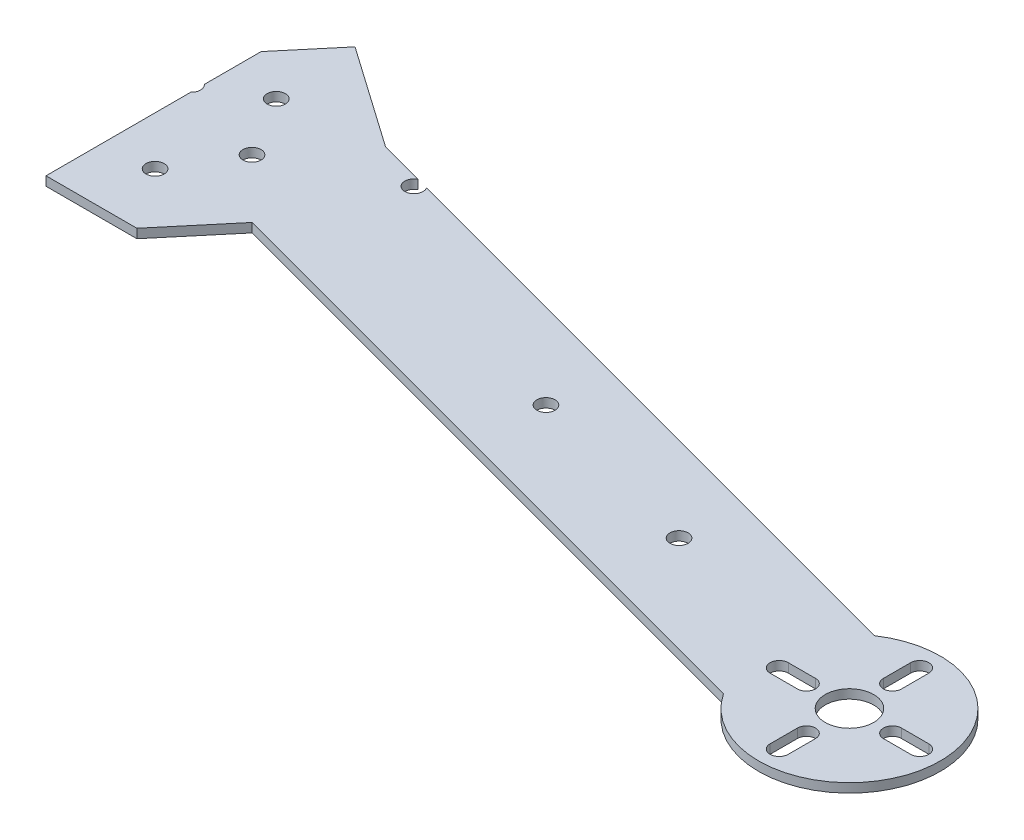
SolidWorks part; units mm, degrees
other "Markup1"
sketch "Sketch5" plane through (0, 1.5, 8.4265) normal (-0.2691, 0.6708, 0.6911) x (0.9345, 0.0084, 0.3557)
ref_plane "Front Plane" through (0, 0, 0) normal (0, 0, 1) x (1, 0, 0)
ref_plane "Top Plane" through (0, 0, 0) normal (0, 1, 0) x (1, 0, 0)
ref_plane "Right Plane" through (0, 0, 0) normal (1, 0, 0) x (0, 0, -1)
sketch "Sketch2" plane through (0, 0, 0) normal (0, 1, 0) x (1, 0, 0)
  line L25 (7.0707, -17.6306) -> (28.2625, -17.6306) construction
  line L26 (142.4295, -80.5981) -> (142.4295, -86.6558) construction
  line L27 (147.7774, -80.5981) -> (142.4295, -80.5981) construction
  line L28 (136.0028, -80.5981) -> (147.7774, -80.5981) construction
  line L29 (23.6776, -60.4195) -> (23.8633, -38.593) construction
  line L30 (0, -46.8792) -> (0, -70.7611)
  line L31 (142.4295, -80.5981) -> (142.4295, -75.2609)
  line L32 (23.8633, -38.593) -> (134.0979, -68.1247)
  line L33 (7.0707, -26.8346) -> (23.8633, -38.593)
  line L34 (0, -35.2611) -> (7.0707, -26.8346)
  line L35 (23.6776, -60.4195) -> (129.9295, -88.8896)
  line L36 (15, -70.7611) -> (23.6776, -60.4195)
  line L37 (0, -70.7611) -> (15, -70.7611)
  line L38 (0, -35.2611) -> (0, -44.6431)
  line L39 (142.4295, -73.4981) -> (142.4295, -68.9981) construction
  line L40 (143.9295, -73.4981) -> (143.9295, -68.9981)
  line L41 (140.9295, -73.4981) -> (140.9295, -68.9981)
  line L42 (149.5295, -80.5981) -> (154.0295, -80.5981) construction
  line L43 (149.5295, -82.0981) -> (154.0295, -82.0981)
  line L44 (149.5295, -79.0981) -> (154.0295, -79.0981)
  line L45 (142.4295, -87.6981) -> (142.4295, -92.1981) construction
  line L46 (140.9295, -87.6981) -> (140.9295, -92.1981)
  line L47 (143.9295, -87.6981) -> (143.9295, -92.1981)
  line L48 (135.3295, -80.5981) -> (130.8295, -80.5981) construction
  line L49 (135.3295, -79.0981) -> (130.8295, -79.0981)
  line L50 (135.3295, -82.0981) -> (130.8295, -82.0981)
  arc A14 (0, -44.6431) -> (0, -46.8792) centre (-1, -45.7611) cw
  circle A15 centre (8, -40.7611) radius 1.5
  circle A16 centre (14, -50.7611) radius 1.5
  circle A17 centre (8, -60.7611) radius 1.5
  circle A18 centre (142.4295, -80.5981) radius 4
  arc A19 (134.0979, -68.1247) -> (129.9295, -88.8896) centre (142.4295, -80.5981) cw
  arc A20 (143.9295, -73.4981) -> (140.9295, -73.4981) centre (142.4295, -73.4981) cw
  arc A21 (140.9295, -68.9981) -> (143.9295, -68.9981) centre (142.4295, -68.9981) cw
  arc A22 (149.5295, -82.0981) -> (149.5295, -79.0981) centre (149.5295, -80.5981) cw
  arc A23 (154.0295, -79.0981) -> (154.0295, -82.0981) centre (154.0295, -80.5981) cw
  arc A24 (140.9295, -87.6981) -> (143.9295, -87.6981) centre (142.4295, -87.6981) cw
  arc A25 (143.9295, -92.1981) -> (140.9295, -92.1981) centre (142.4295, -92.1981) cw
  arc A26 (135.3295, -79.0981) -> (135.3295, -82.0981) centre (135.3295, -80.5981) cw
  arc A27 (130.8295, -82.0981) -> (130.8295, -79.0981) centre (130.8295, -80.5981) cw
  point P95 (142.4295, -80.5981)
  point P98 (142.4295, -71.2481)
  point P105 (151.7795, -80.5981)
  point P112 (142.4295, -89.9481)
  point P119 (133.0795, -80.5981)
extrude "Boss-Extrude1" add sketch "Sketch2" along normal blind 1.5
sketch "Sketch6" plane through (0, 1.5, 0) normal (0, 1, 0) x (1, 0, 0)
  circle A0 centre (31.86, -41.9011) radius 1.5
  circle A1 centre (14, -50.7611) radius 1.5 construction
  dimension "D1" = 3
  dimension "D2" = 17.86
  dimension "D3" = 8.86
extrude "Cut-Extrude1" cut sketch "Sketch6" against normal up to surface (1.5 mm away) up to face at (133.0795, 0, 80.5981)
sketch "Sketch7" plane through (0, 1.5, 0) normal (0, 1, 0) x (1, 0, 0)
  line L0 (23.8633, -38.593) -> (134.0979, -68.1247) construction
  line L1 (142.4295, -80.5981) -> (23.994, -48.8693) construction
  circle A0 centre (74.0141, -62.2696) radius 1.5
  circle A1 centre (104.0141, -70.3066) radius 1.5
  point P11 (74.6161, -62.4309)
  point P12 (110.19, -71.9611)
  dimension "D1" = 3
  dimension "D2" = 3
  dimension "D3" = 30
  dimension "D4" = 39.77
extrude "Cut-Extrude2" cut sketch "Sketch7" against normal up to surface (1.5 mm away) up to face at (35.2404, 0, 53.3645)
